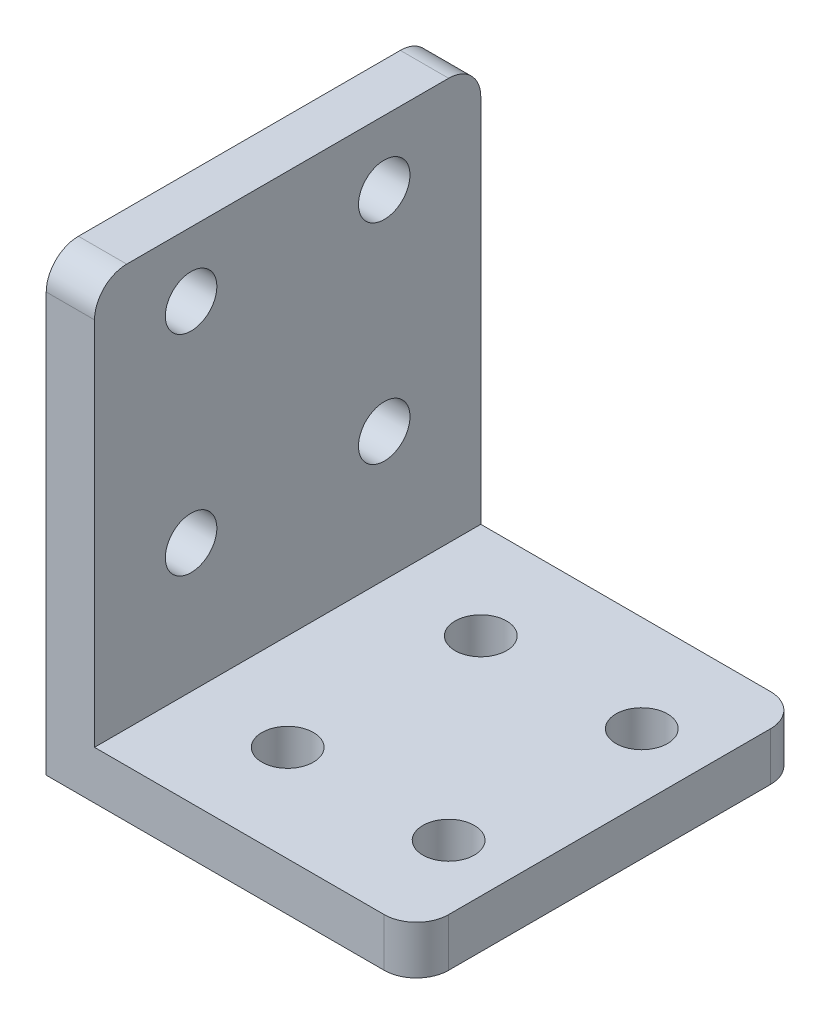
SolidWorks part; units mm, degrees
material "6061 合金"
ref_plane "前视基准面" through (0, 0, 0) normal (0, 0, 1) x (1, 0, 0)
ref_plane "上视基准面" through (0, 0, 0) normal (0, 1, 0) x (1, 0, 0)
ref_plane "右视基准面" through (0, 0, 0) normal (1, 0, 0) x (0, 0, -1)
sketch "草图1" plane through (0, 0, 0) normal (0, 0, 1) x (1, 0, 0)
  line L0 (3, 231.6916) -> (3, 101.6916) construction
  line L1 (3, 129.6916) -> (6, 129.6916)
  line L2 (3, 129.6916) -> (3, -64.3846)
  line L4 (6, 129.6916) -> (6, 104.6916)
  line L6 (3, 101.6916) -> (26, 101.6916)
  line L7 (3, 101.6916) -> (3, -61.5122)
  line L8 (6, 104.6916) -> (26, 104.6916)
  line L9 (26, 101.6916) -> (26, 104.6916)
  dimension "D1" = 3
  dimension "D2" = 3
  dimension "D3" = 25
  dimension "D4" = 20
extrude "凸台-拉伸1" add sketch "草图1" against normal blind 24 contours L6 L9 L8 L4 L1 L2 L7
sketch "草图2" plane through (6, 0, 0) normal (1, 0, 0) x (0, 0, -1)
  line L0 (24, 129.6916) -> (0, 129.6916) construction
  line L1 (0, 129.6916) -> (0, 104.6916) construction
  line L2 (24, 129.6916) -> (24, 104.6916) construction
  circle A0 centre (6, 125.6916) radius 1.6
  circle A1 centre (18, 125.6916) radius 1.6
  dimension "D1" = 3.2
  dimension "D2" = 3.2
  dimension "D3" = 4
  dimension "D4" = 6
  dimension "D5" = 6
  dimension "D6" = 4
extrude "切除-拉伸1" cut sketch "草图2" against normal blind 24
sketch "草图3" plane through (0, 104.6916, 0) normal (0, 1, 0) x (1, 0, 0)
  line L0 (26, 24) -> (26, 0) construction
  line L1 (6, 0) -> (26, 0) construction
  line L2 (6, 24) -> (26, 24) construction
  circle A0 centre (22, 6) radius 1.6
  circle A1 centre (22, 18) radius 1.6
  dimension "D1" = 3.2
  dimension "D2" = 3.2
  dimension "D3" = 4
  dimension "D4" = 4
  dimension "D5" = 6
  dimension "D6" = 6
extrude "切除-拉伸2" cut sketch "草图3" against normal blind 24
fillet "圆角1" radius 2 4 edges at (26, 103.1916, -24) (26, 103.1916, 0) (4.5, 129.6916, -24) (4.5, 129.6916, 0)
sketch "草图4" plane through (3, 0, 0) normal (-1, 0, 0) x (0, 0, 1)
  circle A0 centre (-18, 112.6916) radius 1.6
  circle A1 centre (-6, 112.6916) radius 1.6
extrude "切除-拉伸3" cut sketch "草图4" against normal blind 4
sketch "草图5" plane through (0, 104.6916, 0) normal (0, 1, 0) x (1, 0, 0)
  line L0 (6, 0) -> (24, 0) construction
  line L1 (22, 18) -> (12, 18) construction
  line L2 (22, 18) -> (22, 6) construction
  line L3 (22, 6) -> (12, 6) construction
  line L4 (12, 18) -> (12, 6) construction
  circle A0 centre (12, 18) radius 1.6
  circle A1 centre (12, 6) radius 1.6
  dimension "D4" = 3.2
  dimension "D1" = 12
  dimension "D2" = 6
  dimension "D3" = 10
extrude "切除-拉伸4" cut sketch "草图5" against normal blind 4
